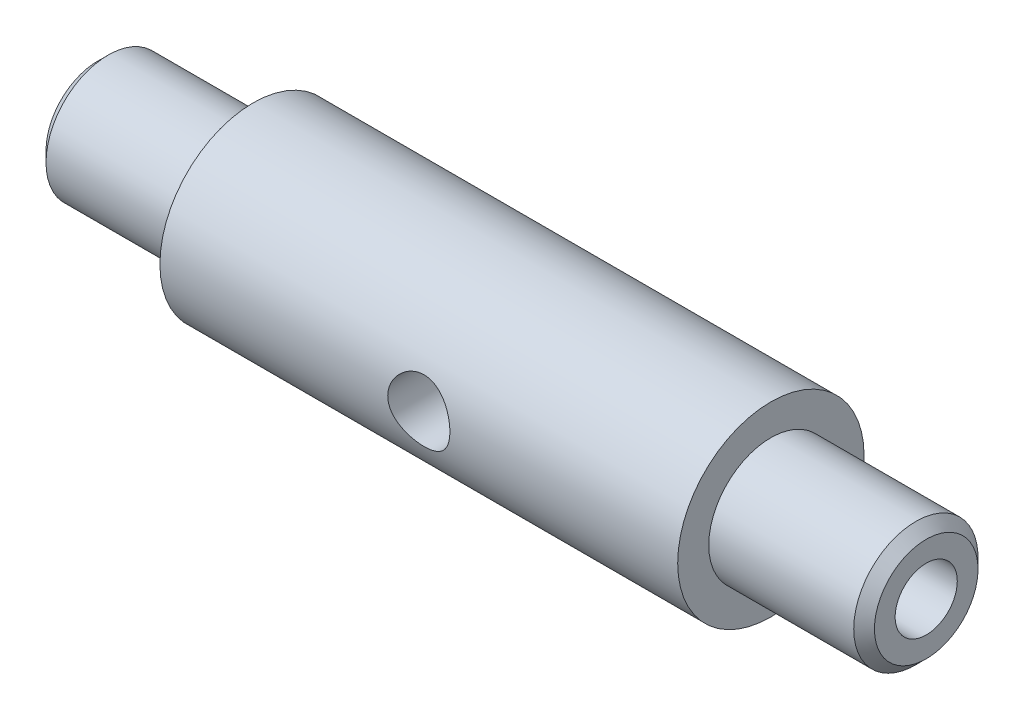
SolidWorks part; units mm, degrees
ref_plane "Front Plane" through (0, 0, 0) normal (0, 0, 1) x (1, 0, 0)
ref_plane "Top Plane" through (0, 0, 0) normal (0, 1, 0) x (1, 0, 0)
ref_plane "Right Plane" through (0, 0, 0) normal (1, 0, 0) x (0, 0, -1)
sketch "Sketch1" plane through (0, 0, 0) normal (0, 0, 1) x (1, 0, 0)
  line L0 (-40, 0) -> (40, 0)
  line L1 (-40, 0) -> (-40, 5)
  line L2 (-39, 6) -> (-25, 6)
  line L3 (-25, 6) -> (-25, 9)
  line L4 (-25, 9) -> (25, 9)
  line L5 (25, 9) -> (25, 6)
  line L6 (25, 6) -> (39, 6)
  line L7 (40, 5) -> (40, 0)
  line L8 (-40, 5) -> (-39, 6)
  line L9 (39, 6) -> (40, 5)
  point P3 (-40, 6)
  point P7 (40, 6)
  dimension "D1" = 40
  dimension "D2" = 40
  dimension "D3" = 25
  dimension "D4" = 25
  dimension "D5" = 6
  dimension "D6" = 6
  dimension "D7" = 1
  dimension "D8" = 45
  dimension "D9" = 1
  dimension "D10" = 45
  dimension "D11" = 9
revolve "Revolve1" add sketch "Sketch1" angle 360 about L0
sketch "Sketch2" plane through (0, 0, 0) normal (0, 0, 1) x (1, 0, 0)
  circle A0 centre (0, 0) radius 3
  dimension "D1" = 6
extrude "Cut-Extrude2" cut sketch "Sketch2" against normal blind 21 and the other way blind 22 contours A0
sketch "Sketch3" plane through (40, 0, 0) normal (1, 0, 0) x (0, 0, -1)
  circle A0 centre (0, 0) radius 3
  dimension "D1" = 6
extrude "Cut-Extrude3" cut sketch "Sketch3" against normal blind 45
